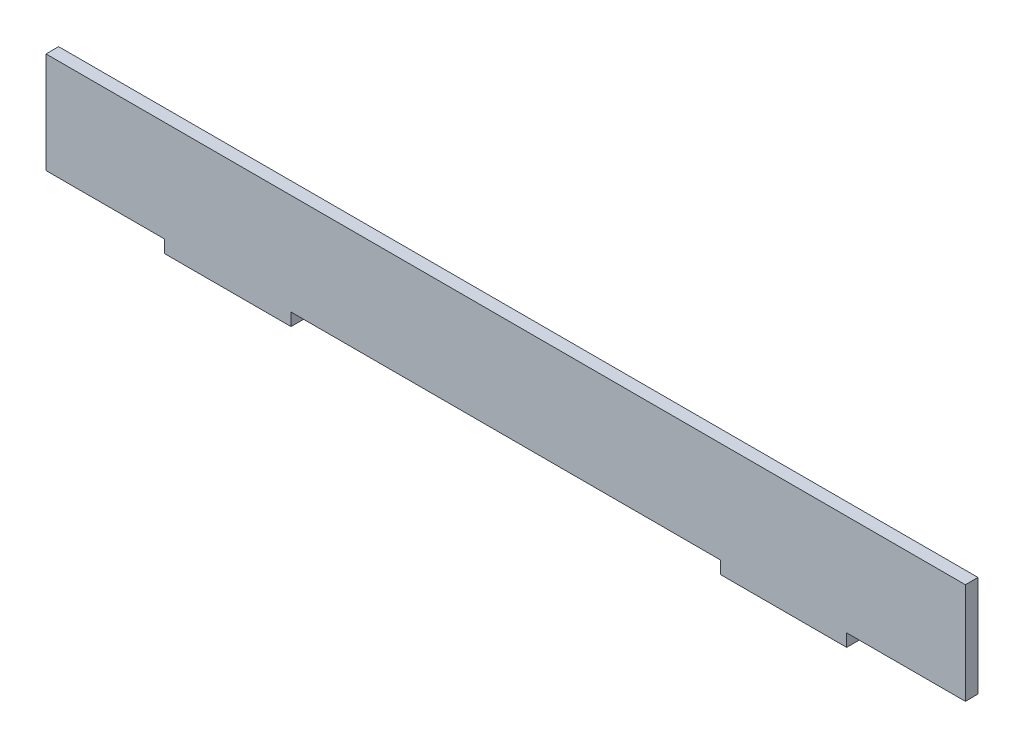
SolidWorks part; units mm, degrees
ref_plane "Plan de face" through (0, 0, 0) normal (0, 0, 1) x (1, 0, 0)
ref_plane "Plan de dessus" through (0, 0, 0) normal (0, 1, 0) x (1, 0, 0)
ref_plane "Plan de droite" through (0, 0, 0) normal (1, 0, 0) x (0, 0, -1)
sketch "Esquisse1" plane through (0, 0, 0) normal (0, 0, 1) x (1, 0, 0)
  line L1 (-182, 20) -> (182, 20)
  line L2 (-182, 20) -> (-182, -20)
  line L3 (-182, -20) -> (182, -20)
  line L4 (182, 20) -> (182, -20)
  line L5 (-182, 20) -> (182, -20) construction
  line L6 (-182, -20) -> (182, 20) construction
  point P0 (0, 0)
  dimension "D1" = 364
  dimension "D2" = 40
extrude "Boss.-Extru.1" add sketch "Esquisse1" along normal blind 5
sketch "Esquisse2" plane through (0, 0, 0) normal (0, 0, -1) x (-1, 0, 0)
  line L0 (182, -20) -> (-182, -20) construction
  line L1 (-85, -25) -> (-135, -25)
  line L2 (-85, -25) -> (-85, -20)
  line L3 (-85, -20) -> (-135, -20)
  line L4 (-135, -25) -> (-135, -20)
  line L5 (-85, -25) -> (-135, -20) construction
  line L6 (-85, -20) -> (-135, -25) construction
  line L7 (0, 58.3957) -> (0, -58.8688) construction
  line L8 (85, -20) -> (135, -20)
  line L9 (135, -25) -> (135, -20)
  line L10 (85, -25) -> (135, -25)
  line L11 (85, -25) -> (85, -20)
  point P0 (-110, -22.5)
  dimension "D1" = 110
  dimension "D2" = 50
  dimension "D3" = 5
extrude "Boss.-Extru.2" add sketch "Esquisse2" against normal blind 5
